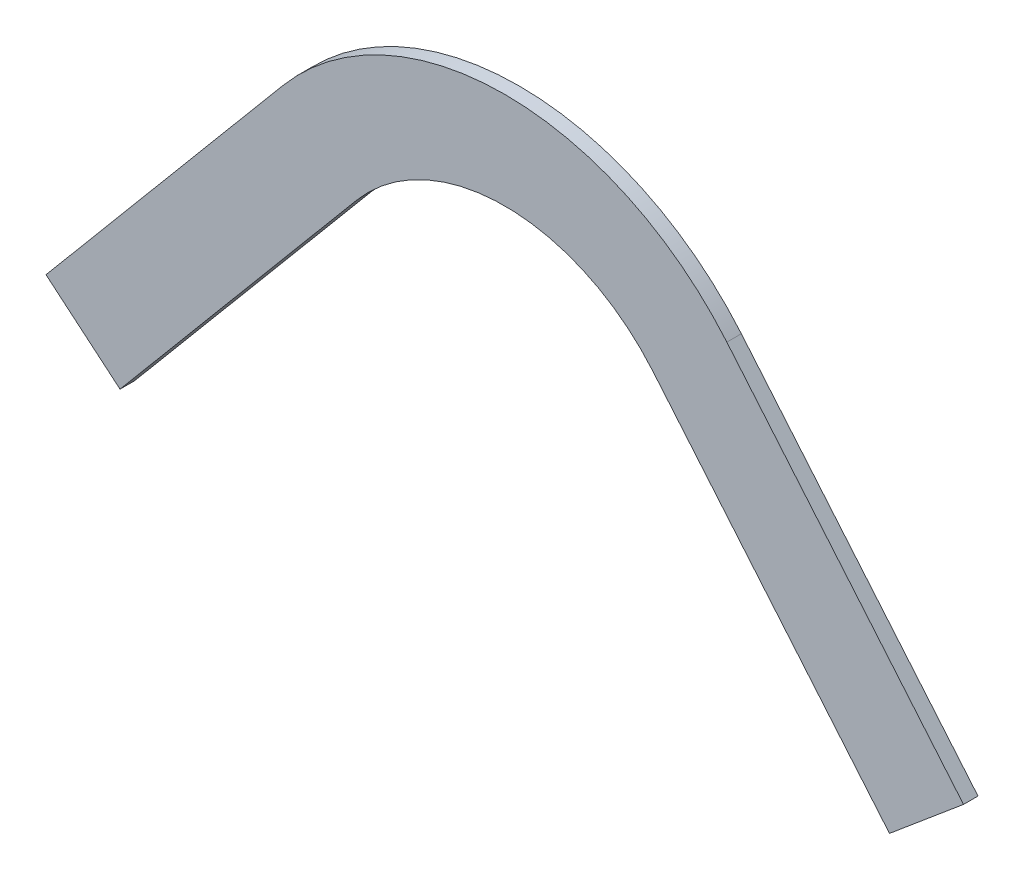
SolidWorks part; units mm, degrees
material "Thornel Mat VMA"
ref_plane "Front Plane" through (0, 0, 0) normal (0, 0, 1) x (1, 0, 0)
ref_plane "Top Plane" through (0, 0, 0) normal (0, 1, 0) x (1, 0, 0)
ref_plane "Right Plane" through (0, 0, 0) normal (1, 0, 0) x (0, 0, -1)
sketch "Sketch1" plane through (0, 0, 0) normal (0, 0, 1) x (1, 0, 0)
  line L0 (-38.3022, 32.1394) -> (0, 0) construction
  line L1 (0, 0) -> (0, 50) construction
  line L2 (38.3022, 32.1394) -> (0, 0) construction
  line L3 (45.9627, 38.5673) -> (30.6418, 25.7115)
  line L4 (-45.9627, 38.5673) -> (-30.6418, 25.7115)
  line L5 (-38.3022, 32.1394) -> (0, 77.7862) construction
  line L6 (-38.3022, 32.1394) -> (0, 32.1394) construction
  arc A0 (38.3022, 32.1394) -> (-38.3022, 32.1394) centre (0, 0) ccw construction
  arc A1 (45.9627, 38.5673) -> (-45.9627, 38.5673) centre (0, 0) ccw
  arc A2 (30.6418, 25.7115) -> (-30.6418, 25.7115) centre (0, 0) ccw
  dimension "D1" = 100
  dimension "D2" = 50
  dimension "D3" = 10
  dimension "D4" = 10
extrude "Boss-Extrude1" add sketch "Sketch1" along normal mid plane 3
ref_plane "Plane1" through (0, 0, 0) normal (-1, 0, 0) x (0, 0, 1)
sketch "Sketch2" plane through (0, 0, 0) normal (-0.6428, -0.766, 0) x (0, 0, 1)
  line L0 (1.5, 60) -> (1.5, 40) construction
  line L1 (1.5, 60) -> (-1.5, 60)
  line L2 (1.5, 60) -> (1.5, 40)
  line L3 (1.5, 40) -> (-1.5, 40)
  line L4 (-1.5, 60) -> (-1.5, 40)
  line L5 (1.5, 60) -> (-1.5, 60) construction
extrude "Boss-Extrude2" add sketch "Sketch2" along normal blind 26.2
mirror "Mirror1" about plane through (0, 0, 0) normal (-1, 0, 0) of "Boss-Extrude2"
sketch "Sketch3" plane through (0, 0, -1.5) normal (0, 0, -1) x (-1, 0, 0)
  line L0 (47.4828, 5.6411) -> (62.8037, 18.4969)
  line L1 (47.4828, 5.6411) -> (79.6222, -32.6611)
  line L2 (62.8037, 18.4969) -> (94.9431, -19.8053)
  line L3 (79.6222, -32.6611) -> (94.9431, -19.8053)
  line L5 (0, 60) -> (0, 40) construction
  line L6 (-79.6222, -32.6611) -> (-94.9431, -19.8053)
  line L7 (-62.8037, 18.4969) -> (-94.9431, -19.8053)
  line L8 (-47.4828, 5.6411) -> (-79.6222, -32.6611)
  line L9 (-47.4828, 5.6411) -> (-62.8037, 18.4969)
  arc A0 (45.9627, 38.5673) -> (-45.9627, 38.5673) centre (0, 0) ccw construction
  arc A1 (30.6418, 25.7115) -> (-30.6418, 25.7115) centre (0, 0) ccw construction
  dimension "D1" = 50
extrude "Boss-Extrude3" add sketch "Sketch3" against normal up to surface (3 mm away) up to face at (0, 26.5694, 1.5)
